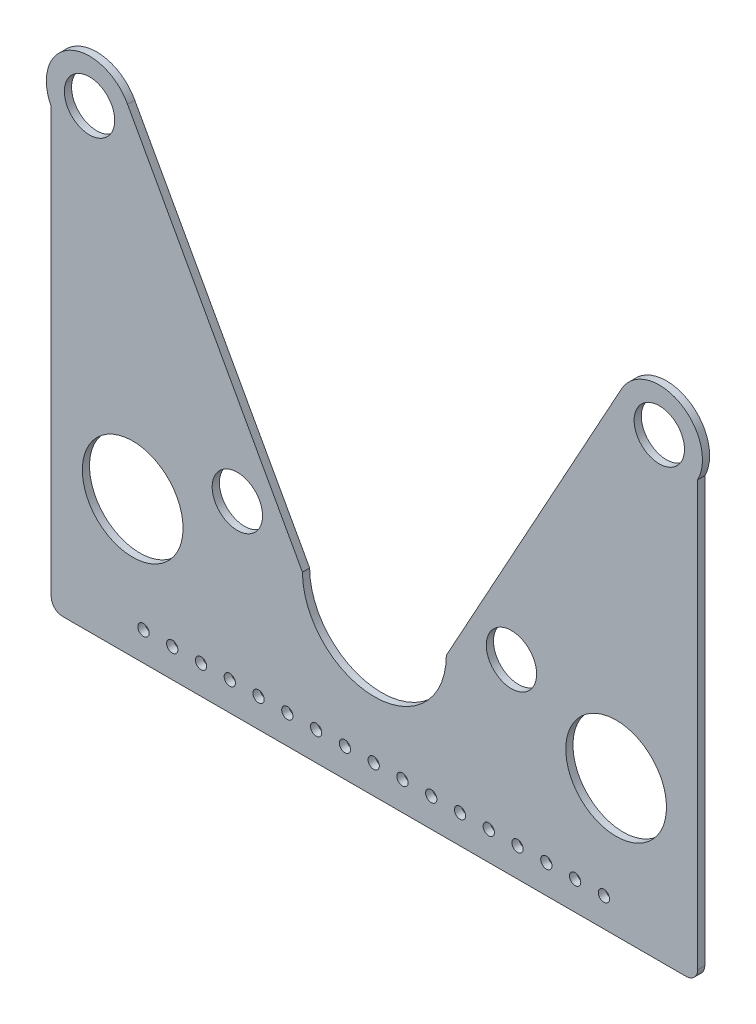
SolidWorks part; units mm, degrees
ref_plane "Front Plane" through (0, 0, 0) normal (0, 0, 1) x (1, 0, 0)
ref_plane "Top Plane" through (0, 0, 0) normal (0, 1, 0) x (1, 0, 0)
ref_plane "Right Plane" through (0, 0, 0) normal (1, 0, 0) x (0, 0, -1)
sketch "Sketch2" plane through (0, 0, 0) normal (0, 0, 1) x (1, 0, 0)
  line L0 (-142.6324, -29.9371) -> (-142.6324, -64.77)
  line L1 (142.6324, 122.4629) -> (142.6324, -29.9371)
  line L3 (31.75, 0) -> (108.9183, 140.209)
  line L4 (0, -1082.0685) -> (0, 1082.0685) construction
  line L5 (-106.68, -44.45) -> (106.68, -44.45) construction
  line L6 (-106.68, -59.1767) -> (-106.68, -31.75)
  line L7 (0, -31.75) -> (106.68, -31.75) construction
  line L8 (106.68, -55.9582) -> (106.68, -31.75)
  line L9 (-31.75, 0) -> (-108.9183, 140.209)
  line L10 (31.75, 0) -> (108.9183, 140.209)
  line L11 (142.6324, -64.77) -> (142.6324, -29.9371)
  line L33 (-106.68, -31.75) -> (0, -31.75) construction
  line L34 (-142.6324, 122.4629) -> (-142.6324, -29.9371)
  line L35 (137.5524, -69.85) -> (-137.5524, -69.85)
  arc A0 (-31.75, 0) -> (31.75, 0) centre (0, 0) ccw
  arc A1 (-108.9183, 140.209) -> (-142.6324, 122.4629) centre (-125.7268, 131.2438) ccw
  circle A2 centre (-60.4845, 12.7) radius 11.1125
  arc A3 (31.75, 0) -> (0, 31.75) centre (0, 0) ccw construction
  arc A4 (0, 31.75) -> (-31.75, 0) centre (0, 0) ccw construction
  arc A5 (137.5524, -69.85) -> (142.6324, -64.77) centre (137.5524, -64.77) ccw
  arc A6 (-137.5524, -69.85) -> (-142.6324, -64.77) centre (-137.5524, -64.77) cw
  circle A7 centre (-125.7268, 131.2438) radius 11.1125
  circle A9 centre (-60.4845, 12.7) radius 19.05 construction
  circle A10 centre (60.4845, 12.7) radius 19.05 construction
  arc A11 (108.9183, 140.209) -> (142.6324, 122.4629) centre (125.7268, 131.2438) cw
  circle A12 centre (125.7268, 131.2438) radius 11.1125
  circle A34 centre (-101.9175, -57.15) radius 2.4892
  arc A40 (-142.6324, 122.4629) -> (-108.9183, 140.209) centre (-125.7268, 131.2438) ccw construction
  arc A41 (142.6324, 122.4629) -> (108.9183, 140.209) centre (125.7268, 131.2438) cw construction
  circle A42 centre (60.4845, 12.7) radius 11.1125
  circle A43 centre (-89.2175, -57.15) radius 2.4892
  circle A44 centre (-76.5175, -57.15) radius 2.4892
  circle A45 centre (-63.8175, -57.15) radius 2.4892
  circle A46 centre (-51.1175, -57.15) radius 2.4892
  circle A47 centre (-38.4175, -57.15) radius 2.4892
  circle A48 centre (-25.7175, -57.15) radius 2.4892
  circle A49 centre (-13.0175, -57.15) radius 2.4892
  circle A50 centre (-0.3175, -57.15) radius 2.4892
  circle A51 centre (12.3825, -57.15) radius 2.4892
  circle A52 centre (25.0825, -57.15) radius 2.4892
  circle A53 centre (37.7825, -57.15) radius 2.4892
  circle A54 centre (50.4825, -57.15) radius 2.4892
  circle A55 centre (63.1825, -57.15) radius 2.4892
  circle A56 centre (75.8825, -57.15) radius 2.4892
  circle A57 centre (88.5825, -57.15) radius 2.4892
  circle A58 centre (101.2825, -57.15) radius 2.4892
  circle A71 centre (-106.68, -9.525) radius 22.225
  circle A72 centre (106.68, -9.525) radius 22.225
  point P0 (142.6324, -68.7497)
  dimension "D7" = 131.2438
  dimension "D8" = 9.525
  dimension "D9" = 25.4
  dimension "D3" = 44.45
  dimension "D14" = 106.68
  dimension "D17" = 38.1
  dimension "D5" = 12.7
  dimension "D15" = 31.75
  dimension "D16" = 22.225
  dimension "D18" = 22.225
  dimension "D19" = 19.05
  dimension "D21" = 125.7268
  dimension "D27" = 44.45
  dimension "D4" = 5.08
  dimension "D1" = 28.828
  dimension "D6" = 101.9175
  dimension "D10" = 17
  dimension "D20" = 142.6324
  dimension "D25" = 152.4
  dimension "D26" = 12.7
extrude "Boss-Extrude1" add sketch "Sketch2" along normal blind 3.175
